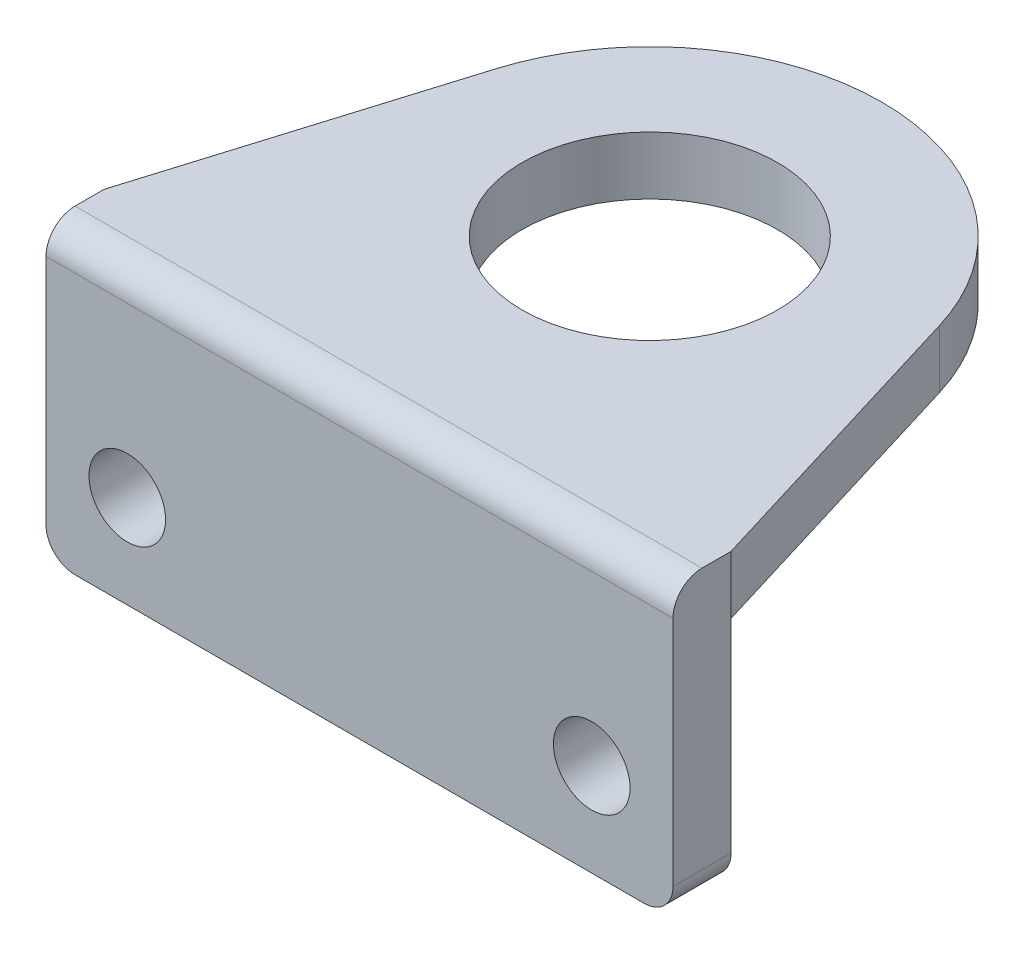
SolidWorks part; units mm, degrees
ref_plane "Alzado" through (0, 0, 0) normal (0, 0, 1) x (1, 0, 0)
ref_plane "Planta" through (0, 0, 0) normal (0, 1, 0) x (1, 0, 0)
ref_plane "Vista lateral" through (0, 0, 0) normal (1, 0, 0) x (0, 0, -1)
sketch "Croquis1" plane through (0, 0, 0) normal (0, 1, 0) x (1, 0, 0)
  line L0 (-27, 0) -> (27, 0)
  line L1 (0, 0) -> (0, 25) construction
  line L2 (0, 0) -> (0, 45) construction
  line L3 (27, 0) -> (27, 5)
  line L4 (27, 5) -> (19.132, 30.8282)
  line L5 (-27, 5) -> (-19.132, 30.8282)
  line L6 (-27, 0) -> (-27, 5)
  arc A0 (19.132, 30.8282) -> (-19.132, 30.8282) centre (0, 25) ccw
  circle A1 centre (0, 25) radius 11
  dimension "D5" = 22
  dimension "D2" = 20
  dimension "D1" = 27
  dimension "D3" = 5
  dimension "D4" = 25
sketch "Croquis2" plane through (0, 0, 0) normal (0, 0, 1) x (1, 0, 0)
  line L0 (-27, 0) -> (27, 0)
  line L1 (-27, 0) -> (-19.132, 0) construction
  line L2 (-27, 0) -> (27, 0) construction
  line L3 (27, 0) -> (19.132, 0) construction
  line L4 (27, 0) -> (27, -25)
  line L5 (27, -25) -> (-27, -25)
  line L6 (-27, -25) -> (-27, 0)
  circle A0 centre (20, -17) radius 3.3
  circle A1 centre (-20, -17) radius 3.3
  dimension "D2" = 6.6
  dimension "D5" = 17
  dimension "D1" = 25
  dimension "D3" = 40
  dimension "D4" = 20
extrude "Saliente-Extruir1" add sketch "Croquis1" against normal blind 5
extrude "Saliente-Extruir2" add sketch "Croquis2" against normal blind 5
fillet "Redondeo1" radius 2.5 1 edges at (0, 0, 0)
fillet "Redondeo2" radius 2.5 2 edges at (27, -25, -2.5) (-27, -25, -2.5)
